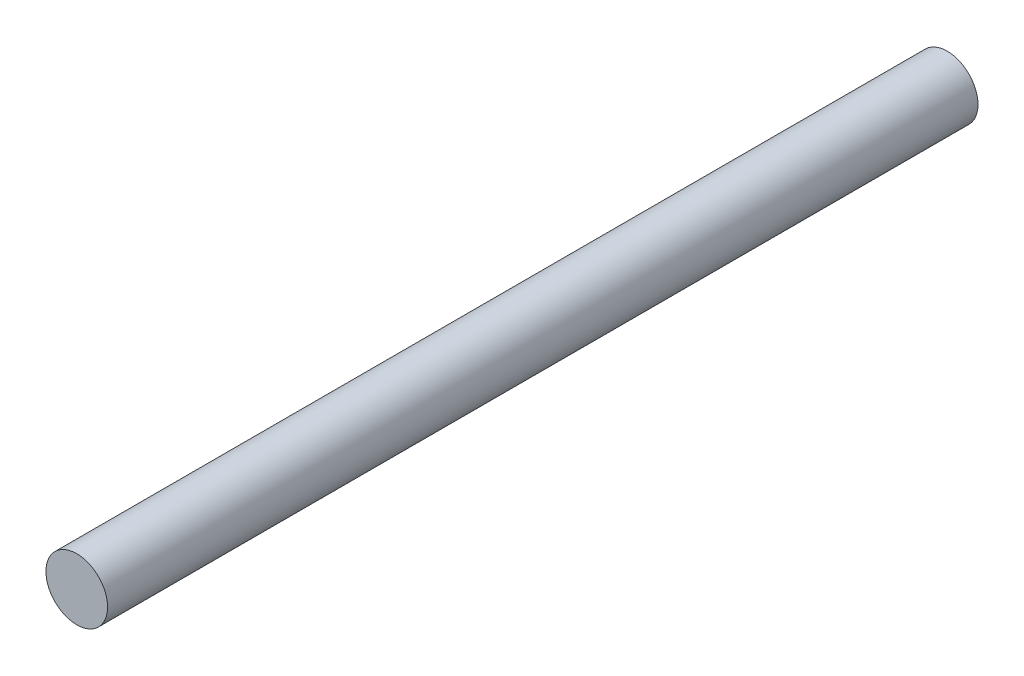
SolidWorks part; units mm, degrees
ref_plane "Alzado" through (0, 0, 0) normal (0, 0, 1) x (1, 0, 0)
ref_plane "Planta" through (0, 0, 0) normal (0, 1, 0) x (1, 0, 0)
ref_plane "Vista lateral" through (0, 0, 0) normal (1, 0, 0) x (0, 0, -1)
sketch "Croquis1" plane through (0, 0, 0) normal (0, 0, 1) x (1, 0, 0)
  circle A0 centre (0, 0) radius 4
  dimension "D1" = 8
extrude "Saliente-Extruir1" add sketch "Croquis1" along normal mid plane 113
ref_plane "Plano2" through (3, 0, 0) normal (1, 0, 0) x (0, 0, -1)
